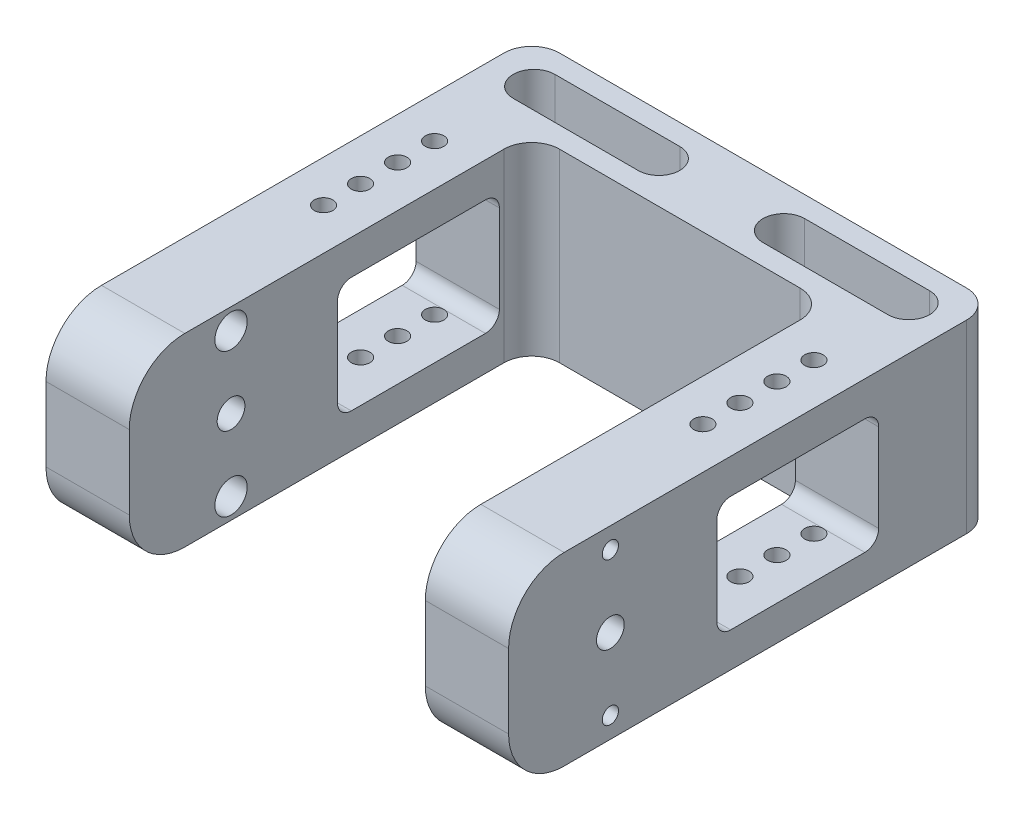
SolidWorks part; units mm, degrees
ref_plane "前视基准面" through (0, 0, 0) normal (0, 0, 1) x (1, 0, 0)
ref_plane "上视基准面" through (0, 0, 0) normal (0, 1, 0) x (1, 0, 0)
ref_plane "右视基准面" through (0, 0, 0) normal (1, 0, 0) x (0, 0, -1)
other "Configuration Table"
sketch "草图1" plane through (0, 0, 0) normal (0, 1, 0) x (1, 0, 0)
  line L0 (-18, 0) -> (0, 0)
  line L9 (-100, 90) -> (0, 90)
  line L10 (-100, 90) -> (-100, 0)
  line L11 (-100, 0) -> (-82, 0)
  line L12 (0, 90) -> (0, 0)
  line L13 (-100, 90) -> (0, 0) construction
  line L14 (-100, 0) -> (0, 90) construction
  line L16 (-82, 0) -> (-82, 72)
  line L17 (-82, 72) -> (-18, 72)
  line L18 (-18, 0) -> (-18, 72)
  point P0 (0, 0)
  point P1 (-50, 45)
  dimension "D1" = 100
  dimension "D2" = 90
  dimension "D3" = 64
  dimension "D4" = 18
  dimension "D5" = 18
extrude "凸台-拉伸1" add sketch "草图1" along normal mid plane 40
sketch "草图2" plane through (-100, 0, 0) normal (-1, 0, 0) x (0, 0, 1)
  circle A0 centre (-7, 0) radius 3
  circle A1 centre (-7, 15.5) radius 1.75
  circle A2 centre (-7, -15.5) radius 1.75
  point P7 (0, 0)
  dimension "D1" = 6
  dimension "D5" = 3.5
  dimension "D6" = 3.5
  dimension "D2" = 7
  dimension "D3" = 15.5
  dimension "D4" = 15.5
extrude "切除-拉伸1" cut sketch "草图2" against normal blind 112
sketch "草图4" plane through (-18, 0, 0) normal (-1, 0, 0) x (0, 0, 1)
  line L0 (0, 20) -> (0, -20) construction
  line L1 (-62, 12.5) -> (-33, 12.5)
  line L2 (-65, 9.5) -> (-65, -9.5)
  line L3 (-62, -12.5) -> (-33, -12.5)
  line L4 (-30, 9.5) -> (-30, -9.5)
  arc A1 (-65, -9.5) -> (-62, -12.5) centre (-62, -9.5) ccw
  arc A2 (-33, -12.5) -> (-30, -9.5) centre (-33, -9.5) ccw
  arc A3 (-33, 12.5) -> (-30, 9.5) centre (-33, 9.5) cw
  arc A4 (-62, 12.5) -> (-65, 9.5) centre (-62, 9.5) ccw
  point P4 (-30, 0)
  point P12 (-30, -12.5)
  point P15 (-30, 12.5)
  point P18 (-65, 12.5)
  dimension "D4" = 3
  dimension "D1" = 35
  dimension "D2" = 30
  dimension "D3" = 25
extrude "切除-拉伸2" cut sketch "草图4" against normal blind 61 and the other way blind 123
sketch "草图5" plane through (0, 0, 0) normal (0, 0, 1) x (1, 0, 0)
  line L0 (-18, -20) -> (0, -20) construction
  line L1 (0, -20) -> (0, 20) construction
  line L2 (0, 20) -> (-18, 20) construction
  line L3 (-18, 20) -> (-18, -20) construction
  line L4 (-100, -20) -> (-82, -20) construction
  line L5 (-82, -20) -> (-82, 20) construction
  line L6 (-82, 20) -> (-100, 20) construction
  line L7 (-100, 20) -> (-100, -20) construction
  line L8 (-18, -20) -> (0, -20)
  line L9 (0, -20) -> (0, 20)
  line L10 (0, 20) -> (-18, 20)
  line L11 (-18, 20) -> (-18, -20)
  line L12 (-100, -20) -> (-82, -20)
  line L13 (-82, -20) -> (-82, 20)
  line L14 (-82, 20) -> (-100, 20)
  line L15 (-100, 20) -> (-100, -20)
extrude "凸台-拉伸3" add sketch "草图5" along normal blind 15
sketch "草图6" plane through (0, 20, 0) normal (0, 1, 0) x (1, 0, 0)
  line L0 (-50, 90) -> (-50, -20.2588) construction
  line L1 (0, 90) -> (-100, 90) construction
  line L2 (-82, -15) -> (-82, 72) construction
  line L3 (-82, 72) -> (-18, 72) construction
  circle A0 centre (-91, 60) radius 2
  circle A1 centre (-91, 52) radius 2
  circle A2 centre (-91, 44) radius 2
  circle A3 centre (-91, 36) radius 2
  circle A4 centre (-9, 36) radius 2
  circle A5 centre (-9, 44) radius 2
  circle A6 centre (-9, 52) radius 2
  circle A7 centre (-9, 60) radius 2
  dimension "D3" = 4
  dimension "D1" = 9
  dimension "D2" = 12
  dimension "D5" = 8
  dimension "D4" = 4
extrude "切除-拉伸3" cut sketch "草图6" against normal through all both and the other way through all
sketch "草图7" plane through (0, 20, 0) normal (0, 1, 0) x (1, 0, 0)
  line L0 (-50, 90) -> (-50, 18.8642) construction
  line L1 (0, 90) -> (-100, 90) construction
  line L2 (-90.5, 81) -> (-63.5, 81) construction
  line L3 (-90.5, 85.5) -> (-63.5, 85.5)
  line L4 (-90.5, 76.5) -> (-63.5, 76.5)
  line L5 (-82, 72) -> (-18, 72) construction
  line L6 (-9.5, 81) -> (-36.5, 81) construction
  line L7 (-9.5, 85.5) -> (-36.5, 85.5)
  line L8 (-9.5, 76.5) -> (-36.5, 76.5)
  arc A0 (-90.5, 85.5) -> (-90.5, 76.5) centre (-90.5, 81) ccw
  arc A1 (-63.5, 76.5) -> (-63.5, 85.5) centre (-63.5, 81) ccw
  arc A2 (-9.5, 85.5) -> (-9.5, 76.5) centre (-9.5, 81) cw
  arc A3 (-36.5, 76.5) -> (-36.5, 85.5) centre (-36.5, 81) cw
  point P2 (-77, 81)
  point P15 (-23, 81)
  dimension "D1" = 9
  dimension "D2" = 9
  dimension "D3" = 27
  dimension "D4" = 27
extrude "切除-拉伸4" cut sketch "草图7" against normal through all both and the other way through all
fillet "圆角1" radius 6 4 edges at (-82, 0, -72) (-18, 0, -72) (0, 0, -90) (-100, 0, -90)
fillet "圆角2" radius 12 4 edges at (-9, -20, 15) (-9, 20, 15) (-91, -20, 15) (-91, 20, 15)
sketch "草图8" plane through (0, 0, -90) normal (0, 0, -1) x (-1, 0, 0)
  line L1 (42.2, -7.8) -> (57.8, -7.8)
  line L2 (42.2, -7.8) -> (42.2, 7.8)
  line L3 (42.2, 7.8) -> (57.8, 7.8)
  line L4 (57.8, -7.8) -> (57.8, 7.8)
  line L5 (42.2, -7.8) -> (57.8, 7.8) construction
  line L6 (42.2, 7.8) -> (57.8, -7.8) construction
  point P0 (50, 0)
  dimension "D1" = 15.6
  dimension "D2" = 50
extrude "切除-拉伸5" cut sketch "草图8" against normal blind 3 and the other way through all
ref_plane "基准面1" through (-50, 0, 0) normal (-1, 0, 0) x (0, 0, 1)
sketch "草图9" plane through (-50, 0, 0) normal (-1, 0, 0) x (0, 0, 1)
  circle A0 centre (-7, 15.5) radius 3.5
  circle A1 centre (-7, -15.5) radius 3.5
  dimension "D1" = 7
  dimension "D2" = 7
extrude "切除-拉伸6" cut sketch "草图9" against normal mid plane 90
